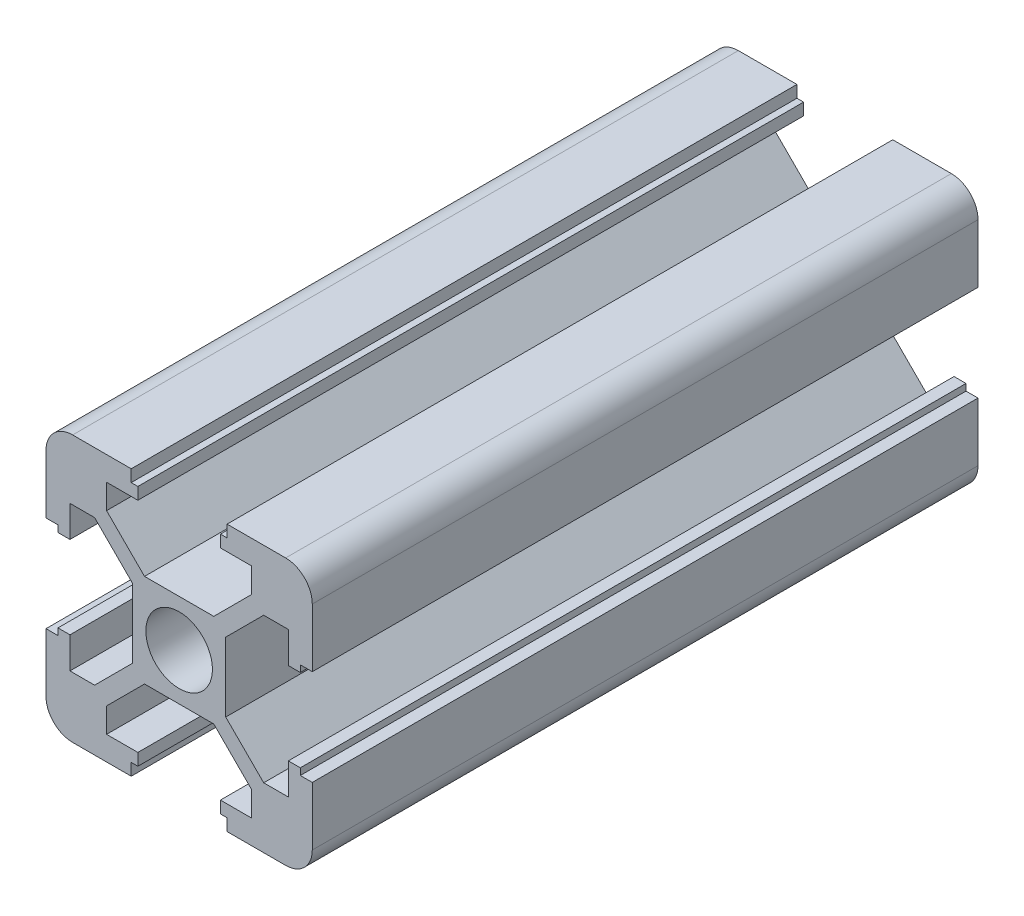
SolidWorks part; units mm, degrees
ref_plane "前视基准面" through (0, 0, 0) normal (0, 0, 1) x (1, 0, 0)
ref_plane "上视基准面" through (0, 0, 0) normal (0, 1, 0) x (1, 0, 0)
ref_plane "右视基准面" through (0, 0, 0) normal (1, 0, 0) x (0, 0, -1)
other "Configuration Table"
sketch "草图1" plane through (0, 0, 0) normal (0, 0, 1) x (1, 0, 0)
  line L5 (-10, 10) -> (10, 10)
  line L6 (-10, 10) -> (-10, -10)
  line L11 (-10, -10) -> (10, -10)
  line L12 (10, 10) -> (10, -10)
  line L25 (-10, 10) -> (10, -10) construction
  line L26 (-10, -10) -> (10, 10) construction
  point P0 (0, 0)
  dimension "D1" = 20
  dimension "D2" = 20
extrude "凸台-拉伸1" add sketch "草图1" along normal blind 50
sketch "草图2" plane through (0, 0, 50) normal (0, 0, 1) x (1, 0, 0)
  line L0 (-10, 0) -> (-8.2, 0)
  line L1 (0, 0) -> (-10, 0)
  line L2 (-11.8, 3.1) -> (-8.2, 3.1)
  line L3 (-11.8, 3.1) -> (-11.8, -3.1)
  line L4 (10, -10) -> (10, 10)
  line L5 (10, 10) -> (-10, 10)
  line L6 (-10, 10) -> (-10, -10)
  line L7 (-10, -10) -> (10, -10)
  line L8 (10, -10) -> (10, 10)
  line L9 (10, 10) -> (-10, 10)
  line L10 (-10, 10) -> (-10, -10)
  line L11 (-10, -10) -> (10, -10)
  line L12 (-11.8, -3.1) -> (-8.2, -3.1)
  line L13 (-8.2, 3.1) -> (-8.2, -3.1)
  line L14 (-11.8, 3.1) -> (-8.2, -3.1) construction
  line L15 (-11.8, -3.1) -> (-8.2, 3.1) construction
  line L16 (-8.2, 5.45) -> (-8.2, -5.45)
  line L17 (-3.5, -2.6) -> (-3.5, 2.6)
  line L18 (-3.5, 3.5) -> (3.5, 3.5)
  line L19 (-3.5, 3.5) -> (-3.5, -3.5)
  line L20 (-3.5, -3.5) -> (3.5, -3.5)
  line L21 (3.5, 3.5) -> (3.5, -3.5)
  line L22 (-3.5, 3.5) -> (3.5, -3.5) construction
  line L23 (-3.5, -3.5) -> (3.5, 3.5) construction
  line L24 (-8.2, 5.45) -> (-6.35, 5.45)
  line L25 (-6.35, 5.45) -> (-3.5, 2.6)
  line L26 (-8.2, -5.45) -> (-6.35, -5.45)
  line L27 (-6.35, -5.45) -> (-3.5, -2.6)
  line L29 (-10.9, -3.6) -> (-9.1, -3.6)
  line L30 (-10.9, -3.6) -> (-10.9, 3.6)
  line L31 (-10.9, 3.6) -> (-9.1, 3.6)
  line L32 (-9.1, -3.6) -> (-9.1, 3.6)
  line L33 (-10.9, -3.6) -> (-9.1, 3.6) construction
  line L34 (-10.9, 3.6) -> (-9.1, -3.6) construction
  circle A0 centre (0, 0) radius 2.5
  point P16 (-8.2, 0)
  point P23 (-3.5, 0)
  dimension "D4" = 5
  dimension "D2" = 1.8
  dimension "D3" = 6.2
  dimension "D5" = 10.9
  dimension "D6" = 7
  dimension "D7" = 7
  dimension "D8" = 5.2
  dimension "D9" = 135
  dimension "D10" = 0.9
  dimension "D11" = 7.2
  dimension "D12" = 135
  dimension "D1" = 0
extrude "切除-拉伸1" cut sketch "草图2" against normal through all
pattern_circular "阵列(圆周)1" count 4 over 360 about axis through (0, 0, 0) along (0, 0, 1) of "切除-拉伸1"
fillet "圆角1" radius 2 4 edges at (-10, -10, 25) (10, -10, 25) (10, 10, 25) (-10, 10, 25)
sketch "草图3" plane through (0, 0, 50) normal (0, 0, 1) x (1, 0, 0)
  line L60 (-10, -3.6) -> (-10, -8)
  line L61 (-8, -10) -> (-3.6, -10)
  line L62 (-3.6, -10) -> (-3.6, -9.1)
  line L63 (-3.6, -9.1) -> (-3.1, -9.1)
  line L64 (-3.1, -9.1) -> (-3.1, -8.2)
  line L65 (-3.1, -8.2) -> (-5.45, -8.2)
  line L66 (-5.45, -8.2) -> (-5.45, -6.35)
  line L67 (-5.45, -6.35) -> (-2.6, -3.5)
  line L68 (-2.6, -3.5) -> (2.6, -3.5)
  line L69 (2.6, -3.5) -> (5.45, -6.35)
  line L70 (5.45, -6.35) -> (5.45, -8.2)
  line L71 (5.45, -8.2) -> (3.1, -8.2)
  line L72 (3.1, -8.2) -> (3.1, -9.1)
  line L73 (3.1, -9.1) -> (3.6, -9.1)
  line L74 (3.6, -9.1) -> (3.6, -10)
  line L75 (3.6, -10) -> (8, -10)
  line L76 (10, -8) -> (10, -3.6)
  line L77 (10, -3.6) -> (9.1, -3.6)
  line L78 (9.1, -3.6) -> (9.1, -3.1)
  line L79 (9.1, -3.1) -> (8.2, -3.1)
  line L80 (8.2, -3.1) -> (8.2, -5.45)
  line L81 (8.2, -5.45) -> (6.35, -5.45)
  line L82 (6.35, -5.45) -> (3.5, -2.6)
  line L83 (3.5, -2.6) -> (3.5, 2.6)
  line L84 (3.5, 2.6) -> (6.35, 5.45)
  line L85 (6.35, 5.45) -> (8.2, 5.45)
  line L86 (8.2, 5.45) -> (8.2, 3.1)
  line L87 (8.2, 3.1) -> (9.1, 3.1)
  line L88 (9.1, 3.1) -> (9.1, 3.6)
  line L89 (9.1, 3.6) -> (10, 3.6)
  line L90 (10, 3.6) -> (10, 8)
  line L91 (8, 10) -> (3.6, 10)
  line L92 (3.6, 10) -> (3.6, 9.1)
  line L93 (3.6, 9.1) -> (3.1, 9.1)
  line L94 (3.1, 9.1) -> (3.1, 8.2)
  line L95 (3.1, 8.2) -> (5.45, 8.2)
  line L96 (5.45, 8.2) -> (5.45, 6.35)
  line L97 (5.45, 6.35) -> (2.6, 3.5)
  line L98 (2.6, 3.5) -> (-2.6, 3.5)
  line L99 (-2.6, 3.5) -> (-5.45, 6.35)
  line L100 (-5.45, 6.35) -> (-5.45, 8.2)
  line L101 (-5.45, 8.2) -> (-3.1, 8.2)
  line L102 (-3.1, 8.2) -> (-3.1, 9.1)
  line L103 (-3.1, 9.1) -> (-3.6, 9.1)
  line L104 (-3.6, 9.1) -> (-3.6, 10)
  line L105 (-3.6, 10) -> (-8, 10)
  line L106 (-10, 8) -> (-10, 3.6)
  line L107 (-10, 3.6) -> (-9.1, 3.6)
  line L108 (-9.1, 3.6) -> (-9.1, 3.1)
  line L109 (-9.1, 3.1) -> (-8.2, 3.1)
  line L110 (-8.2, 3.1) -> (-8.2, 5.45)
  line L111 (-8.2, 5.45) -> (-6.35, 5.45)
  line L112 (-6.35, 5.45) -> (-3.5, 2.6)
  line L113 (-3.5, 2.6) -> (-3.5, -2.6)
  line L114 (-3.5, -2.6) -> (-6.35, -5.45)
  line L115 (-6.35, -5.45) -> (-8.2, -5.45)
  line L116 (-8.2, -5.45) -> (-8.2, -3.1)
  line L117 (-8.2, -3.1) -> (-9.1, -3.1)
  line L118 (-9.1, -3.1) -> (-9.1, -3.6)
  line L119 (-9.1, -3.6) -> (-10, -3.6)
  line L120 (-10, -3.6) -> (-10, -8)
  line L121 (-8, -10) -> (-3.6, -10)
  line L122 (-3.6, -10) -> (-3.6, -9.1)
  line L123 (-3.6, -9.1) -> (-3.1, -9.1)
  line L124 (-3.1, -9.1) -> (-3.1, -8.2)
  line L125 (-3.1, -8.2) -> (-5.45, -8.2)
  line L126 (-5.45, -8.2) -> (-5.45, -6.35)
  line L127 (-5.45, -6.35) -> (-2.6, -3.5)
  line L128 (-2.6, -3.5) -> (2.6, -3.5)
  line L129 (2.6, -3.5) -> (5.45, -6.35)
  line L130 (5.45, -6.35) -> (5.45, -8.2)
  line L131 (5.45, -8.2) -> (3.1, -8.2)
  line L132 (3.1, -8.2) -> (3.1, -9.1)
  line L133 (3.1, -9.1) -> (3.6, -9.1)
  line L134 (3.6, -9.1) -> (3.6, -10)
  line L135 (3.6, -10) -> (8, -10)
  line L136 (10, -8) -> (10, -3.6)
  line L137 (10, -3.6) -> (9.1, -3.6)
  line L138 (9.1, -3.6) -> (9.1, -3.1)
  line L139 (9.1, -3.1) -> (8.2, -3.1)
  line L140 (8.2, -3.1) -> (8.2, -5.45)
  line L141 (8.2, -5.45) -> (6.35, -5.45)
  line L142 (6.35, -5.45) -> (3.5, -2.6)
  line L143 (3.5, -2.6) -> (3.5, 2.6)
  line L144 (3.5, 2.6) -> (6.35, 5.45)
  line L145 (6.35, 5.45) -> (8.2, 5.45)
  line L146 (8.2, 5.45) -> (8.2, 3.1)
  line L147 (8.2, 3.1) -> (9.1, 3.1)
  line L148 (9.1, 3.1) -> (9.1, 3.6)
  line L149 (9.1, 3.6) -> (10, 3.6)
  line L150 (10, 3.6) -> (10, 8)
  line L151 (8, 10) -> (3.6, 10)
  line L152 (3.6, 10) -> (3.6, 9.1)
  line L153 (3.6, 9.1) -> (3.1, 9.1)
  line L154 (3.1, 9.1) -> (3.1, 8.2)
  line L155 (3.1, 8.2) -> (5.45, 8.2)
  line L156 (5.45, 8.2) -> (5.45, 6.35)
  line L157 (5.45, 6.35) -> (2.6, 3.5)
  line L158 (2.6, 3.5) -> (-2.6, 3.5)
  line L159 (-2.6, 3.5) -> (-5.45, 6.35)
  line L160 (-5.45, 6.35) -> (-5.45, 8.2)
  line L161 (-5.45, 8.2) -> (-3.1, 8.2)
  line L162 (-3.1, 8.2) -> (-3.1, 9.1)
  line L163 (-3.1, 9.1) -> (-3.6, 9.1)
  line L164 (-3.6, 9.1) -> (-3.6, 10)
  line L165 (-3.6, 10) -> (-8, 10)
  line L166 (-10, 8) -> (-10, 3.6)
  line L167 (-10, 3.6) -> (-9.1, 3.6)
  line L168 (-9.1, 3.6) -> (-9.1, 3.1)
  line L169 (-9.1, 3.1) -> (-8.2, 3.1)
  line L170 (-8.2, 3.1) -> (-8.2, 5.45)
  line L171 (-8.2, 5.45) -> (-6.35, 5.45)
  line L172 (-6.35, 5.45) -> (-3.5, 2.6)
  line L173 (-3.5, 2.6) -> (-3.5, -2.6)
  line L174 (-3.5, -2.6) -> (-6.35, -5.45)
  line L175 (-6.35, -5.45) -> (-8.2, -5.45)
  line L176 (-8.2, -5.45) -> (-8.2, -3.1)
  line L177 (-8.2, -3.1) -> (-9.1, -3.1)
  line L178 (-9.1, -3.1) -> (-9.1, -3.6)
  line L179 (-9.1, -3.6) -> (-10, -3.6)
  arc A4 (-10, -8) -> (-8, -10) centre (-8, -8) ccw
  arc A5 (8, -10) -> (10, -8) centre (8, -8) ccw
  arc A6 (10, 8) -> (8, 10) centre (8, 8) ccw
  arc A7 (-8, 10) -> (-10, 8) centre (-8, 8) ccw
  arc A8 (-10, -8) -> (-8, -10) centre (-8, -8) ccw
  arc A9 (8, -10) -> (10, -8) centre (8, -8) ccw
  arc A10 (10, 8) -> (8, 10) centre (8, 8) ccw
  arc A11 (-8, 10) -> (-10, 8) centre (-8, 8) ccw
  dimension "D1" = 0
